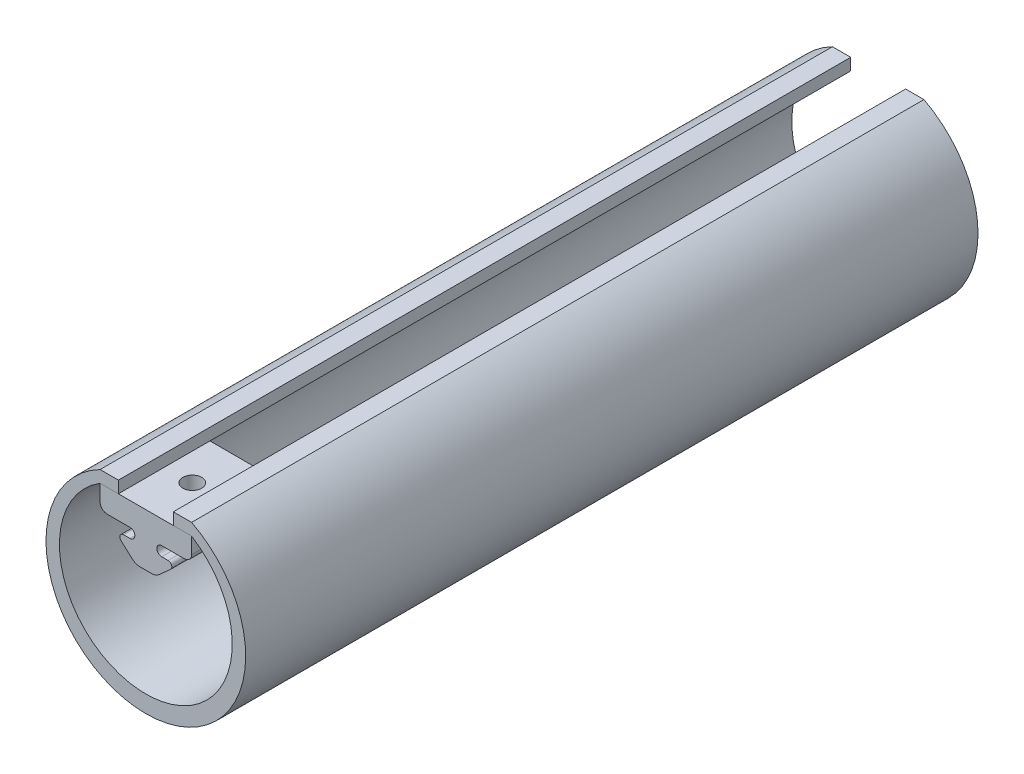
SolidWorks part; units mm, degrees
material "6105-T5 Aluminum"
ref_plane "Front Plane" through (0, 0, 0) normal (0, 0, 1) x (1, 0, 0)
ref_plane "Top Plane" through (0, 0, 0) normal (0, 1, 0) x (1, 0, 0)
ref_plane "Right Plane" through (0, 0, 0) normal (1, 0, 0) x (0, 0, -1)
sketch "Sketch1" plane through (0, 0, 0) normal (0, 0, 1) x (1, 0, 0)
  line L14 (4.315, 12.745) -> (10.5321, 12.745)
  line L15 (12.505, 14.7079) -> (12.505, 19.095)
  line L16 (6.085, 10.115) -> (4.315, 10.115)
  line L17 (3.6646, 5.583) -> (6.7586, 8.3524)
  line L28 (1.5504, 4.775) -> (-1.5504, 4.775)
  line L29 (-3.6646, 5.583) -> (-6.7586, 8.3524)
  line L30 (-6.085, 10.115) -> (-4.315, 10.115)
  line L31 (-12.495, 14.7079) -> (-12.495, 19.095)
  line L32 (-4.315, 12.745) -> (-10.5321, 12.745)
  line L36 (-15.7643, 0) -> (12.505, 0) construction
  line L37 (0, 13.9334) -> (0, -12.3541) construction
  line L38 (-12.495, 19.095) -> (12.505, 19.095)
  arc A12 (4.315, 10.115) -> (4.315, 12.745) centre (4.315, 11.43) cw
  arc A13 (6.085, 10.115) -> (6.7586, 8.3524) centre (6.085, 9.105) cw
  arc A14 (3.6646, 5.583) -> (1.5504, 4.775) centre (1.5504, 7.945) cw
  arc A24 (-3.6646, 5.583) -> (-1.5504, 4.775) centre (-1.5504, 7.945) ccw
  arc A25 (-6.085, 10.115) -> (-6.7586, 8.3524) centre (-6.085, 9.105) ccw
  arc A26 (-4.315, 10.115) -> (-4.315, 12.745) centre (-4.315, 11.43) ccw
  arc A29 (10.5321, 12.745) -> (12.505, 14.7079) centre (10.5421, 14.7079) ccw
  arc A30 (-10.5321, 12.745) -> (-12.495, 14.7079) centre (-10.5321, 14.7079) cw
  dimension "D4" = 14.19
  dimension "D5" = 5.34
  dimension "D6" = 6
  dimension "D7" = 1.01
  dimension "D8" = 6.35
  dimension "D3" = 3.17
  dimension "D2" = 25
  dimension "D10" = 2.63
extrude "Extrude1" add sketch "Sketch1" against normal blind 25
sketch "Sketch2" plane through (0, 19.095, 0) normal (0, 1, 0) x (1, 0, 0)
  line L0 (0, 50.8) -> (0, 0) construction
  line L3 (-12.495, 25) -> (-12.495, 0) construction
  line L4 (-12.495, 12.5) -> (12.5, 12.5) construction
  circle A1 centre (0, 12.7) radius 2.5797
extrude "Cut-Extrude1" cut sketch "Sketch2" against normal through all
sketch "Sketch5" plane through (0, 0, 0) normal (0, 0, 1) x (1, 0, 0)
  line L0 (-12.495, 19.095) -> (-12.495, 22.3324)
  line L1 (-12.495, 22.3324) -> (-7.495, 22.3324)
  line L2 (12.505, 22.3324) -> (12.505, 19.095)
  line L3 (-7.495, 22.3324) -> (-7.495, 19.095)
  line L4 (12.505, 19.095) -> (-12.495, 19.095) construction
  line L5 (7.505, 22.3324) -> (7.505, 19.095)
  line L6 (-12.495, 22.3324) -> (-7.495, 22.3324)
  line L7 (-7.495, 19.095) -> (-12.495, 19.095)
  line L8 (7.505, 22.3324) -> (12.505, 22.3324)
  line L9 (12.505, 19.095) -> (7.505, 19.095)
  line L10 (7.505, 22.3324) -> (12.505, 22.3324)
  arc A0 (-12.495, 19.095) -> (12.505, 19.095) centre (0.005, -0.9197) ccw
  arc A1 (-12.495, 22.3324) -> (12.505, 22.3324) centre (0.005, -1.9007) ccw
  line M3 (12.505, 19.095) -> (-12.495, 19.095)
  dimension "D1" = 5
  dimension "D2" = 5
extrude "Boss-Extrude1" add sketch "Sketch5" against normal blind 200 separate body contours L0 A1 L2 A0 | L3 L1 L0 M3 | L8 L5 L2 M3
